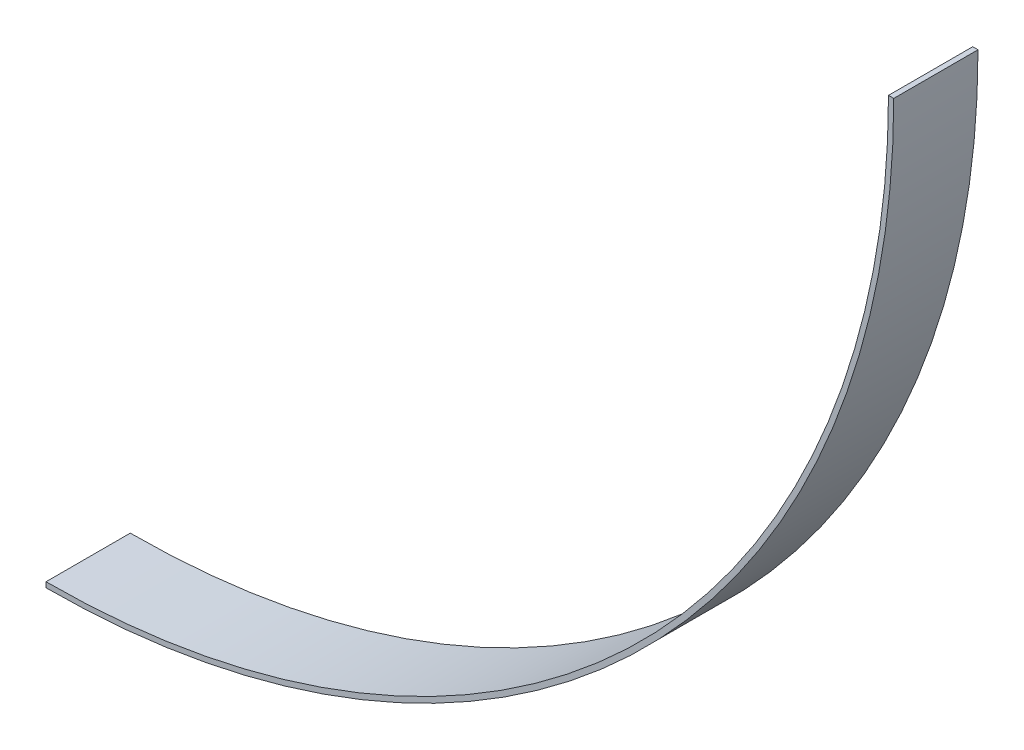
SolidWorks part; units mm, degrees
ref_plane "Front Plane" through (0, 0, 0) normal (0, 0, 1) x (1, 0, 0)
ref_plane "Top Plane" through (0, 0, 0) normal (0, 1, 0) x (1, 0, 0)
ref_plane "Right Plane" through (0, 0, 0) normal (1, 0, 0) x (0, 0, -1)
sketch "Sketch1" plane through (0, 0, 0) normal (0, 0, 1) x (1, 0, 0)
  line L0 (0, -254) -> (0, -255.5875)
  line L1 (254, 0) -> (255.5875, 0)
  arc A0 (0, -254) -> (254, 0) centre (0, 0) ccw
  arc A1 (0, -255.5875) -> (255.5875, 0) centre (0, 0) ccw
  dimension "D1" = 1.5875
extrude "Boss-Extrude1" add sketch "Sketch1" along normal blind 25.4
